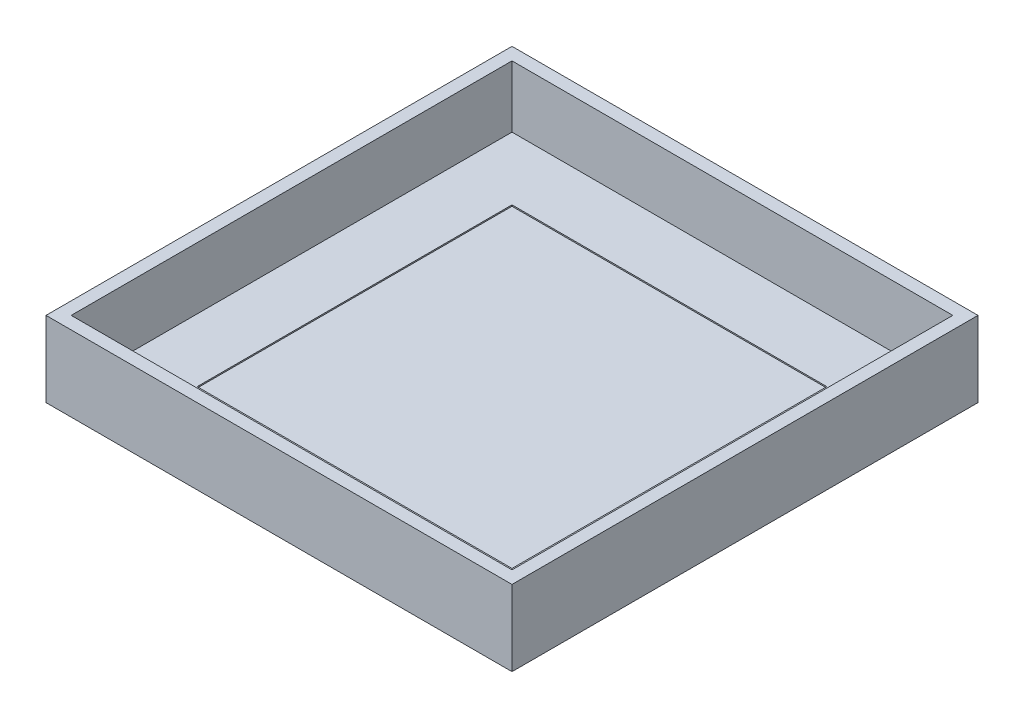
SolidWorks part; units mm, degrees
ref_plane "前视基准面" through (0, 0, 0) normal (0, 0, 1) x (1, 0, 0)
ref_plane "上视基准面" through (0, 0, 0) normal (0, 1, 0) x (1, 0, 0)
ref_plane "右视基准面" through (0, 0, 0) normal (1, 0, 0) x (0, 0, -1)
sketch "草图1" plane through (0, 0, 0) normal (0, 1, 0) x (1, 0, 0)
  line L1 (-175, 175) -> (175, 175)
  line L2 (-175, 175) -> (-175, -175)
  line L3 (-175, -175) -> (175, -175)
  line L4 (175, 175) -> (175, -175)
  line L5 (-175, 175) -> (175, -175) construction
  line L6 (-175, -175) -> (175, 175) construction
  line L7 (-185, 185) -> (185, 185)
  line L8 (-185, 185) -> (-185, -185)
  line L9 (-185, -185) -> (185, -185)
  line L10 (185, 185) -> (185, -185)
  line L11 (-185, 185) -> (185, -185) construction
  line L12 (-185, -185) -> (185, 185) construction
  point P0 (0, 0)
  point P6 (0, 0)
  dimension "D1" = 350
  dimension "D2" = 10
extrude "凸台-拉伸1" add sketch "草图1" along normal blind 50
sketch "草图2" plane through (0, 0, 0) normal (0, -1, 0) x (1, 0, 0)
  line L1 (-185, 185) -> (185, 185)
  line L2 (-185, 185) -> (-185, -185)
  line L3 (-185, -185) -> (185, -185)
  line L4 (185, 185) -> (185, -185)
extrude "凸台-拉伸2" add sketch "草图2" along normal blind 10
sketch "草图3" plane through (0, 0, 0) normal (0, 1, 0) x (1, 0, 0)
  line L0 (175, 175) -> (-175, 175) construction
  line L1 (-125, 125) -> (125, 125)
  line L2 (-125, 125) -> (-125, -125)
  line L3 (-125, -125) -> (125, -125)
  line L4 (125, 125) -> (125, -125)
  line L5 (-125, 125) -> (125, -125) construction
  line L6 (-125, -125) -> (125, 125) construction
  line L7 (175, -175) -> (175, 175) construction
  line L9 (-175, 175) -> (175, 175)
  line L10 (-175, 175) -> (-175, -175)
  line L11 (-175, -175) -> (175, -175)
  line L12 (175, 175) -> (175, -175)
  point P0 (0, 0)
  dimension "D1" = 50
  dimension "D2" = 50
extrude "凸台-拉伸3" add sketch "草图3" along normal blind 1
